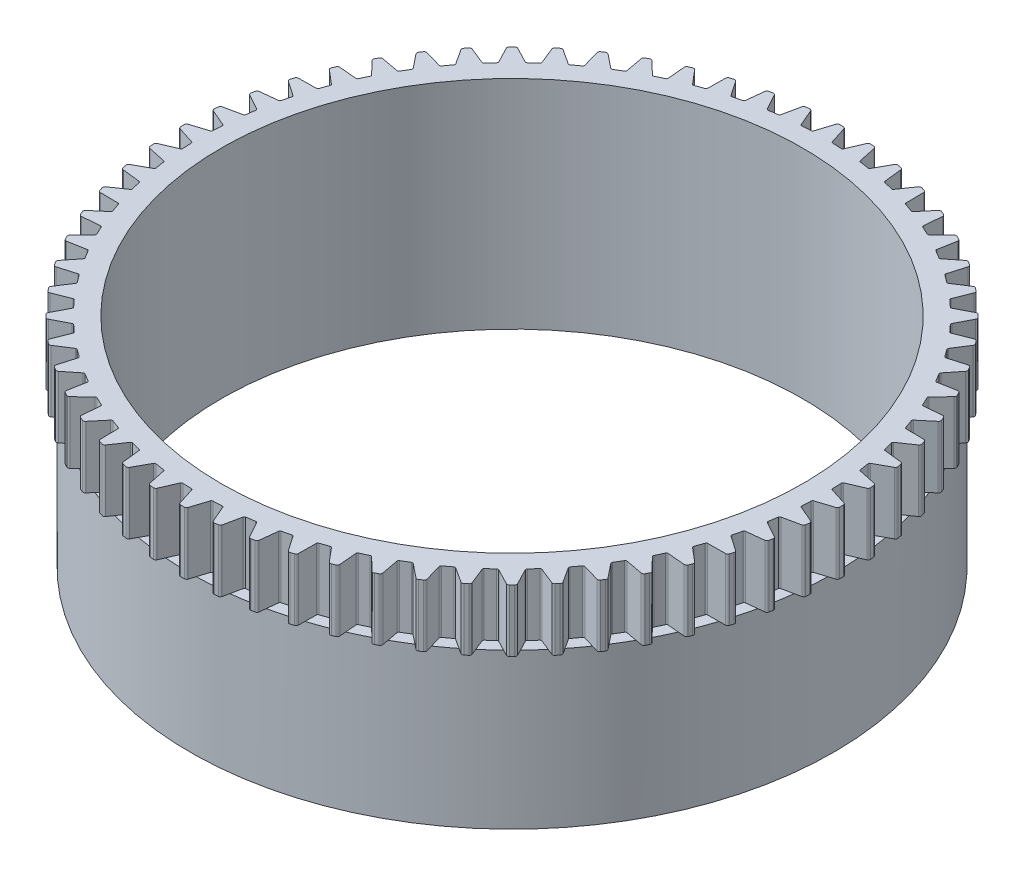
SolidWorks part; units mm, degrees
ref_plane "Front Plane" through (0, 0, 0) normal (0, 0, 1) x (1, 0, 0)
ref_plane "Top Plane" through (0, 0, 0) normal (0, 1, 0) x (1, 0, 0)
ref_plane "Right Plane" through (0, 0, 0) normal (1, 0, 0) x (0, 0, -1)
sketch "Sketch1" plane through (0, 0, 0) normal (0, 1, 0) x (1, 0, 0)
  line L0 (0, 53.7167) -> (0, -50.4595) construction
  line L1 (-0.5164, 42.2908) -> (-1.2072, 40.1152)
  line L2 (-0.2305, 42.5) -> (0.2305, 42.5)
  line L3 (0.5164, 42.2908) -> (1.2072, 40.1152)
  line L4 (3.6313, 42.1378) -> (2.7306, 40.0403)
  line L5 (4.6592, 42.0365) -> (5.1334, 39.8037)
  line L6 (3.9363, 42.3179) -> (4.3951, 42.2728)
  line L7 (7.744, 41.5789) -> (6.642, 39.5799)
  line L8 (8.757, 41.3774) -> (9.0101, 39.1088)
  line L9 (8.0653, 41.7283) -> (8.5174, 41.6384)
  line L10 (11.7822, 40.6197) -> (10.4896, 38.7383)
  line L11 (12.7706, 40.3199) -> (12.8001, 38.0374)
  line L12 (12.1165, 40.7369) -> (12.5577, 40.6031)
  line L13 (15.7069, 39.2692) -> (14.2361, 37.5236)
  line L14 (16.6611, 38.874) -> (16.4667, 36.5996)
  line L15 (16.0511, 39.3531) -> (16.477, 39.1767)
  line L16 (19.4803, 37.5406) -> (17.8455, 35.9475)
  line L17 (20.3912, 37.0537) -> (19.9748, 34.8093)
  line L18 (19.8311, 37.5903) -> (20.2376, 37.373)
  line L19 (23.0661, 35.4504) -> (21.283, 34.0252)
  line L20 (23.9249, 34.8766) -> (23.2906, 32.6838)
  line L21 (23.4201, 35.4655) -> (23.8034, 35.2094)
  line L22 (26.4298, 33.0188) -> (24.5156, 31.7753)
  line L23 (27.2282, 32.3636) -> (26.382, 30.2436)
  line L24 (26.7835, 32.9992) -> (27.1399, 32.7067)
  line L25 (29.5389, 30.2693) -> (27.5121, 29.2193)
  line L26 (30.2693, 29.5389) -> (29.2193, 27.5121)
  line L27 (29.8891, 30.215) -> (30.215, 29.8891)
  line L28 (32.3636, 27.2282) -> (30.2436, 26.382)
  line L29 (33.0188, 26.4298) -> (31.7753, 24.5156)
  line L30 (32.7067, 27.1399) -> (32.9992, 26.7835)
  line L31 (34.8766, 23.9249) -> (32.6838, 23.2906)
  line L32 (35.4504, 23.0661) -> (34.0252, 21.283)
  line L33 (35.2094, 23.8034) -> (35.4655, 23.4201)
  line L34 (37.0537, 20.3912) -> (34.8093, 19.9748)
  line L35 (37.5406, 19.4803) -> (35.9475, 17.8455)
  line L36 (37.373, 20.2376) -> (37.5903, 19.8311)
  line L37 (38.874, 16.6611) -> (36.5996, 16.4667)
  line L38 (39.2692, 15.7069) -> (37.5236, 14.2361)
  line L39 (39.1767, 16.477) -> (39.3531, 16.0511)
  line L40 (40.3199, 12.7706) -> (38.0374, 12.8001)
  line L41 (40.6197, 11.7822) -> (38.7383, 10.4896)
  line L42 (40.6031, 12.5577) -> (40.7369, 12.1165)
  line L43 (41.3774, 8.757) -> (39.1088, 9.0101)
  line L44 (41.5789, 7.744) -> (39.5799, 6.642)
  line L45 (41.6384, 8.5174) -> (41.7283, 8.0653)
  line L46 (42.0365, 4.6592) -> (39.8037, 5.1334)
  line L47 (42.1378, 3.6313) -> (40.0403, 2.7306)
  line L48 (42.2728, 4.3951) -> (42.3179, 3.9363)
  line L49 (42.2908, 0.5164) -> (40.1152, 1.2072)
  line L50 (42.2908, -0.5164) -> (40.1152, -1.2072)
  line L51 (42.5, 0.2305) -> (42.5, -0.2305)
  line L52 (42.1378, -3.6313) -> (40.0403, -2.7306)
  line L53 (42.0365, -4.6592) -> (39.8037, -5.1334)
  line L54 (42.3179, -3.9363) -> (42.2728, -4.3951)
  line L55 (41.5789, -7.744) -> (39.5799, -6.642)
  line L56 (41.3774, -8.757) -> (39.1088, -9.0101)
  line L57 (41.7283, -8.0653) -> (41.6384, -8.5174)
  line L58 (40.6197, -11.7822) -> (38.7383, -10.4896)
  line L59 (40.3199, -12.7706) -> (38.0374, -12.8001)
  line L60 (40.7369, -12.1165) -> (40.6031, -12.5577)
  line L61 (39.2692, -15.7069) -> (37.5236, -14.2361)
  line L62 (38.874, -16.6611) -> (36.5996, -16.4667)
  line L63 (39.3531, -16.0511) -> (39.1767, -16.477)
  line L64 (37.5406, -19.4803) -> (35.9475, -17.8455)
  line L65 (37.0537, -20.3912) -> (34.8093, -19.9748)
  line L66 (37.5903, -19.8311) -> (37.373, -20.2376)
  line L67 (35.4504, -23.0661) -> (34.0252, -21.283)
  line L68 (34.8766, -23.9249) -> (32.6838, -23.2906)
  line L69 (35.4655, -23.4201) -> (35.2094, -23.8034)
  line L70 (33.0188, -26.4298) -> (31.7753, -24.5156)
  line L71 (32.3636, -27.2282) -> (30.2436, -26.382)
  line L72 (32.9992, -26.7835) -> (32.7067, -27.1399)
  line L73 (30.2693, -29.5389) -> (29.2193, -27.5121)
  line L74 (29.5389, -30.2693) -> (27.5121, -29.2193)
  line L75 (30.215, -29.8891) -> (29.8891, -30.215)
  line L76 (27.2282, -32.3636) -> (26.382, -30.2436)
  line L77 (26.4298, -33.0188) -> (24.5156, -31.7753)
  line L78 (27.1399, -32.7067) -> (26.7835, -32.9992)
  line L79 (23.9249, -34.8766) -> (23.2906, -32.6838)
  line L80 (23.0661, -35.4504) -> (21.283, -34.0252)
  line L81 (23.8034, -35.2094) -> (23.4201, -35.4655)
  line L82 (20.3912, -37.0537) -> (19.9748, -34.8093)
  line L83 (19.4803, -37.5406) -> (17.8455, -35.9475)
  line L84 (20.2376, -37.373) -> (19.8311, -37.5903)
  line L85 (16.6611, -38.874) -> (16.4667, -36.5996)
  line L86 (15.7069, -39.2692) -> (14.2361, -37.5236)
  line L87 (16.477, -39.1767) -> (16.0511, -39.3531)
  line L88 (12.7706, -40.3199) -> (12.8001, -38.0374)
  line L89 (11.7822, -40.6197) -> (10.4896, -38.7383)
  line L90 (12.5577, -40.6031) -> (12.1165, -40.7369)
  line L91 (8.757, -41.3774) -> (9.0101, -39.1088)
  line L92 (7.744, -41.5789) -> (6.642, -39.5799)
  line L93 (8.5174, -41.6384) -> (8.0653, -41.7283)
  line L94 (4.6592, -42.0365) -> (5.1334, -39.8037)
  line L95 (3.6313, -42.1378) -> (2.7306, -40.0403)
  line L96 (4.3951, -42.2728) -> (3.9363, -42.3179)
  line L97 (0.5164, -42.2908) -> (1.2072, -40.1152)
  line L98 (-0.5164, -42.2908) -> (-1.2072, -40.1152)
  line L99 (0.2305, -42.5) -> (-0.2305, -42.5)
  line L100 (-3.6313, -42.1378) -> (-2.7306, -40.0403)
  line L101 (-4.6592, -42.0365) -> (-5.1334, -39.8037)
  line L102 (-3.9363, -42.3179) -> (-4.3951, -42.2728)
  line L103 (-7.744, -41.5789) -> (-6.642, -39.5799)
  line L104 (-8.757, -41.3774) -> (-9.0101, -39.1088)
  line L105 (-8.0653, -41.7283) -> (-8.5174, -41.6384)
  line L106 (-11.7822, -40.6197) -> (-10.4896, -38.7383)
  line L107 (-12.7706, -40.3199) -> (-12.8001, -38.0374)
  line L108 (-12.1165, -40.7369) -> (-12.5577, -40.6031)
  line L109 (-15.7069, -39.2692) -> (-14.2361, -37.5236)
  line L110 (-16.6611, -38.874) -> (-16.4667, -36.5996)
  line L111 (-16.0511, -39.3531) -> (-16.477, -39.1767)
  line L112 (-19.4803, -37.5406) -> (-17.8455, -35.9475)
  line L113 (-20.3912, -37.0537) -> (-19.9748, -34.8093)
  line L114 (-19.8311, -37.5903) -> (-20.2376, -37.373)
  line L115 (-23.0661, -35.4504) -> (-21.283, -34.0252)
  line L116 (-23.9249, -34.8766) -> (-23.2906, -32.6838)
  line L117 (-23.4201, -35.4655) -> (-23.8034, -35.2094)
  line L118 (-26.4298, -33.0188) -> (-24.5156, -31.7753)
  line L119 (-27.2282, -32.3636) -> (-26.382, -30.2436)
  line L120 (-26.7835, -32.9992) -> (-27.1399, -32.7067)
  line L121 (-29.5389, -30.2693) -> (-27.5121, -29.2193)
  line L122 (-30.2693, -29.5389) -> (-29.2193, -27.5121)
  line L123 (-29.8891, -30.215) -> (-30.215, -29.8891)
  line L124 (-32.3636, -27.2282) -> (-30.2436, -26.382)
  line L125 (-33.0188, -26.4298) -> (-31.7753, -24.5156)
  line L126 (-32.7067, -27.1399) -> (-32.9992, -26.7835)
  line L127 (-34.8766, -23.9249) -> (-32.6838, -23.2906)
  line L128 (-35.4504, -23.0661) -> (-34.0252, -21.283)
  line L129 (-35.2094, -23.8034) -> (-35.4655, -23.4201)
  line L130 (-37.0537, -20.3912) -> (-34.8093, -19.9748)
  line L131 (-37.5406, -19.4803) -> (-35.9475, -17.8455)
  line L132 (-37.373, -20.2376) -> (-37.5903, -19.8311)
  line L133 (-38.874, -16.6611) -> (-36.5996, -16.4667)
  line L134 (-39.2692, -15.7069) -> (-37.5236, -14.2361)
  line L135 (-39.1767, -16.477) -> (-39.3531, -16.0511)
  line L136 (-40.3199, -12.7706) -> (-38.0374, -12.8001)
  line L137 (-40.6197, -11.7822) -> (-38.7383, -10.4896)
  line L138 (-40.6031, -12.5577) -> (-40.7369, -12.1165)
  line L139 (-41.3774, -8.757) -> (-39.1088, -9.0101)
  line L140 (-41.5789, -7.744) -> (-39.5799, -6.642)
  line L141 (-41.6384, -8.5174) -> (-41.7283, -8.0653)
  line L142 (-42.0365, -4.6592) -> (-39.8037, -5.1334)
  line L143 (-42.1378, -3.6313) -> (-40.0403, -2.7306)
  line L144 (-42.2728, -4.3951) -> (-42.3179, -3.9363)
  line L145 (-42.2908, -0.5164) -> (-40.1152, -1.2072)
  line L146 (-42.2908, 0.5164) -> (-40.1152, 1.2072)
  line L147 (-42.5, -0.2305) -> (-42.5, 0.2305)
  line L148 (-42.1378, 3.6313) -> (-40.0403, 2.7306)
  line L149 (-42.0365, 4.6592) -> (-39.8037, 5.1334)
  line L150 (-42.3179, 3.9363) -> (-42.2728, 4.3951)
  line L151 (-41.5789, 7.744) -> (-39.5799, 6.642)
  line L152 (-41.3774, 8.757) -> (-39.1088, 9.0101)
  line L153 (-41.7283, 8.0653) -> (-41.6384, 8.5174)
  line L154 (-40.6197, 11.7822) -> (-38.7383, 10.4896)
  line L155 (-40.3199, 12.7706) -> (-38.0374, 12.8001)
  line L156 (-40.7369, 12.1165) -> (-40.6031, 12.5577)
  line L157 (-39.2692, 15.7069) -> (-37.5236, 14.2361)
  line L158 (-38.874, 16.6611) -> (-36.5996, 16.4667)
  line L159 (-39.3531, 16.0511) -> (-39.1767, 16.477)
  line L160 (-37.5406, 19.4803) -> (-35.9475, 17.8455)
  line L161 (-37.0537, 20.3912) -> (-34.8093, 19.9748)
  line L162 (-37.5903, 19.8311) -> (-37.373, 20.2376)
  line L163 (-35.4504, 23.0661) -> (-34.0252, 21.283)
  line L164 (-34.8766, 23.9249) -> (-32.6838, 23.2906)
  line L165 (-35.4655, 23.4201) -> (-35.2094, 23.8034)
  line L166 (-33.0188, 26.4298) -> (-31.7753, 24.5156)
  line L167 (-32.3636, 27.2282) -> (-30.2436, 26.382)
  line L168 (-32.9992, 26.7835) -> (-32.7067, 27.1399)
  line L169 (-30.2693, 29.5389) -> (-29.2193, 27.5121)
  line L170 (-29.5389, 30.2693) -> (-27.5121, 29.2193)
  line L171 (-30.215, 29.8891) -> (-29.8891, 30.215)
  line L172 (-27.2282, 32.3636) -> (-26.382, 30.2436)
  line L173 (-26.4298, 33.0188) -> (-24.5156, 31.7753)
  line L174 (-27.1399, 32.7067) -> (-26.7835, 32.9992)
  line L175 (-23.9249, 34.8766) -> (-23.2906, 32.6838)
  line L176 (-23.0661, 35.4504) -> (-21.283, 34.0252)
  line L177 (-23.8034, 35.2094) -> (-23.4201, 35.4655)
  line L178 (-20.3912, 37.0537) -> (-19.9748, 34.8093)
  line L179 (-19.4803, 37.5406) -> (-17.8455, 35.9475)
  line L180 (-20.2376, 37.373) -> (-19.8311, 37.5903)
  line L181 (-16.6611, 38.874) -> (-16.4667, 36.5996)
  line L182 (-15.7069, 39.2692) -> (-14.2361, 37.5236)
  line L183 (-16.477, 39.1767) -> (-16.0511, 39.3531)
  line L184 (-12.7706, 40.3199) -> (-12.8001, 38.0374)
  line L185 (-11.7822, 40.6197) -> (-10.4896, 38.7383)
  line L186 (-12.5577, 40.6031) -> (-12.1165, 40.7369)
  line L187 (-8.757, 41.3774) -> (-9.0101, 39.1088)
  line L188 (-7.744, 41.5789) -> (-6.642, 39.5799)
  line L189 (-8.5174, 41.6384) -> (-8.0653, 41.7283)
  line L190 (-4.6592, 42.0365) -> (-5.1334, 39.8037)
  line L191 (-3.6313, 42.1378) -> (-2.7306, 40.0403)
  line L192 (-4.3951, 42.2728) -> (-3.9363, 42.3179)
  arc A0 (-1.3909, 39.9758) -> (-2.5341, 39.9196) centre (0, 0) ccw
  arc A1 (-0.5164, 42.2908) -> (-0.2305, 42.5) centre (-0.2305, 42.2) cw
  arc A2 (0.2305, 42.5) -> (0.5164, 42.2908) centre (0.2305, 42.2) cw
  arc A3 (1.2072, 40.1152) -> (1.3909, 39.9758) centre (1.3979, 40.1757) ccw
  arc A4 (-1.2072, 40.1152) -> (-1.3909, 39.9758) centre (-1.3979, 40.1757) cw
  arc A5 (2.7306, 40.0403) -> (2.5341, 39.9196) centre (2.5468, 40.1192) cw
  arc A6 (5.1334, 39.8037) -> (5.3025, 39.647) centre (5.329, 39.8452) ccw
  arc A7 (4.3951, 42.2728) -> (4.6592, 42.0365) centre (4.3657, 41.9742) cw
  arc A8 (3.6313, 42.1378) -> (3.9363, 42.3179) centre (3.9069, 42.0194) cw
  arc A9 (6.642, 39.5799) -> (6.4347, 39.479) centre (6.4669, 39.6764) cw
  arc A10 (9.0101, 39.1088) -> (9.1631, 38.9363) centre (9.2089, 39.131) ccw
  arc A11 (8.5174, 41.6384) -> (8.757, 41.3774) centre (8.4589, 41.3442) cw
  arc A12 (7.744, 41.5789) -> (8.0653, 41.7283) centre (8.0067, 41.4341) cw
  arc A13 (10.4896, 38.7383) -> (10.2734, 38.6582) centre (10.3247, 38.8515) cw
  arc A14 (12.8001, 38.0374) -> (12.9354, 37.8507) centre (13, 38.04) ccw
  arc A15 (12.5577, 40.6031) -> (12.7706, 40.3199) centre (12.4706, 40.316) cw
  arc A16 (11.7822, 40.6197) -> (12.1165, 40.7369) centre (12.0294, 40.4498) cw
  arc A17 (14.2361, 37.5236) -> (14.0131, 37.4651) centre (14.0831, 37.6524) cw
  arc A18 (16.4667, 36.5996) -> (16.5831, 36.4006) centre (16.666, 36.5826) ccw
  arc A19 (16.477, 39.1767) -> (16.6611, 38.874) centre (16.3622, 38.8995) cw
  arc A20 (15.7069, 39.2692) -> (16.0511, 39.3531) centre (15.9363, 39.0759) cw
  arc A21 (17.8455, 35.9475) -> (17.6178, 35.9112) centre (17.7059, 36.0907) cw
  arc A22 (19.9748, 34.8093) -> (20.0711, 34.5999) centre (20.1715, 34.7729) ccw
  arc A23 (20.2376, 37.373) -> (20.3912, 37.0537) centre (20.0962, 37.1084) cw
  arc A24 (19.4803, 37.5406) -> (19.8311, 37.5903) centre (19.6897, 37.3257) cw
  arc A25 (21.283, 34.0252) -> (21.0529, 34.0114) centre (21.1581, 34.1815) cw
  arc A26 (23.2906, 32.6838) -> (23.3659, 32.4659) centre (23.4827, 32.6283) ccw
  arc A27 (23.8034, 35.2094) -> (23.9249, 34.8766) centre (23.6367, 34.96) cw
  arc A28 (23.0661, 35.4504) -> (23.4201, 35.4655) centre (23.2534, 35.2161) cw
  arc A29 (24.5156, 31.7753) -> (24.2852, 31.7841) centre (24.4066, 31.943) cw
  arc A30 (26.382, 30.2436) -> (26.4356, 30.0193) centre (26.5677, 30.1694) ccw
  arc A31 (27.1399, 32.7067) -> (27.2282, 32.3636) centre (26.9496, 32.4748) cw
  arc A32 (26.4298, 33.0188) -> (26.7835, 32.9992) centre (26.5932, 32.7673) cw
  arc A33 (27.5121, 29.2193) -> (27.2837, 29.2507) centre (27.4201, 29.3969) cw
  arc A34 (29.2193, 27.5121) -> (29.2507, 27.2837) centre (29.3969, 27.4201) ccw
  arc A35 (30.215, 29.8891) -> (30.2693, 29.5389) centre (30.0029, 29.6769) cw
  arc A36 (29.5389, 30.2693) -> (29.8891, 30.215) centre (29.6769, 30.0029) cw
  arc A37 (30.2436, 26.382) -> (30.0193, 26.4356) centre (30.1694, 26.5677) cw
  arc A38 (31.7753, 24.5156) -> (31.7841, 24.2852) centre (31.943, 24.4066) ccw
  arc A39 (32.9992, 26.7835) -> (33.0188, 26.4298) centre (32.7673, 26.5932) cw
  arc A40 (32.3636, 27.2282) -> (32.7067, 27.1399) centre (32.4748, 26.9496) cw
  arc A41 (32.6838, 23.2906) -> (32.4659, 23.3659) centre (32.6283, 23.4827) cw
  arc A42 (34.0252, 21.283) -> (34.0114, 21.0529) centre (34.1815, 21.1581) ccw
  arc A43 (35.4655, 23.4201) -> (35.4504, 23.0661) centre (35.2161, 23.2534) cw
  arc A44 (34.8766, 23.9249) -> (35.2094, 23.8034) centre (34.96, 23.6367) cw
  arc A45 (34.8093, 19.9748) -> (34.5999, 20.0711) centre (34.7729, 20.1715) cw
  arc A46 (35.9475, 17.8455) -> (35.9112, 17.6178) centre (36.0907, 17.7059) ccw
  arc A47 (37.5903, 19.8311) -> (37.5406, 19.4803) centre (37.3257, 19.6897) cw
  arc A48 (37.0537, 20.3912) -> (37.373, 20.2376) centre (37.1084, 20.0962) cw
  arc A49 (36.5996, 16.4667) -> (36.4006, 16.5831) centre (36.5826, 16.666) cw
  arc A50 (37.5236, 14.2361) -> (37.4651, 14.0131) centre (37.6524, 14.0831) ccw
  arc A51 (39.3531, 16.0511) -> (39.2692, 15.7069) centre (39.0759, 15.9363) cw
  arc A52 (38.874, 16.6611) -> (39.1767, 16.477) centre (38.8995, 16.3622) cw
  arc A53 (38.0374, 12.8001) -> (37.8507, 12.9354) centre (38.04, 13) cw
  arc A54 (38.7383, 10.4896) -> (38.6582, 10.2734) centre (38.8515, 10.3247) ccw
  arc A55 (40.7369, 12.1165) -> (40.6197, 11.7822) centre (40.4498, 12.0294) cw
  arc A56 (40.3199, 12.7706) -> (40.6031, 12.5577) centre (40.316, 12.4706) cw
  arc A57 (39.1088, 9.0101) -> (38.9363, 9.1631) centre (39.131, 9.2089) cw
  arc A58 (39.5799, 6.642) -> (39.479, 6.4347) centre (39.6764, 6.4669) ccw
  arc A59 (41.7283, 8.0653) -> (41.5789, 7.744) centre (41.4341, 8.0067) cw
  arc A60 (41.3774, 8.757) -> (41.6384, 8.5174) centre (41.3442, 8.4589) cw
  arc A61 (39.8037, 5.1334) -> (39.647, 5.3025) centre (39.8452, 5.329) cw
  arc A62 (40.0403, 2.7306) -> (39.9196, 2.5341) centre (40.1192, 2.5468) ccw
  arc A63 (42.3179, 3.9363) -> (42.1378, 3.6313) centre (42.0194, 3.9069) cw
  arc A64 (42.0365, 4.6592) -> (42.2728, 4.3951) centre (41.9742, 4.3657) cw
  arc A65 (40.1152, 1.2072) -> (39.9758, 1.3909) centre (40.1757, 1.3979) cw
  arc A66 (40.1152, -1.2072) -> (39.9758, -1.3909) centre (40.1757, -1.3979) ccw
  arc A67 (42.5, -0.2305) -> (42.2908, -0.5164) centre (42.2, -0.2305) cw
  arc A68 (42.2908, 0.5164) -> (42.5, 0.2305) centre (42.2, 0.2305) cw
  arc A69 (40.0403, -2.7306) -> (39.9196, -2.5341) centre (40.1192, -2.5468) cw
  arc A70 (39.8037, -5.1334) -> (39.647, -5.3025) centre (39.8452, -5.329) ccw
  arc A71 (42.2728, -4.3951) -> (42.0365, -4.6592) centre (41.9742, -4.3657) cw
  arc A72 (42.1378, -3.6313) -> (42.3179, -3.9363) centre (42.0194, -3.9069) cw
  arc A73 (39.5799, -6.642) -> (39.479, -6.4347) centre (39.6764, -6.4669) cw
  arc A74 (39.1088, -9.0101) -> (38.9363, -9.1631) centre (39.131, -9.2089) ccw
  arc A75 (41.6384, -8.5174) -> (41.3774, -8.757) centre (41.3442, -8.4589) cw
  arc A76 (41.5789, -7.744) -> (41.7283, -8.0653) centre (41.4341, -8.0067) cw
  arc A77 (38.7383, -10.4896) -> (38.6582, -10.2734) centre (38.8515, -10.3247) cw
  arc A78 (38.0374, -12.8001) -> (37.8507, -12.9354) centre (38.04, -13) ccw
  arc A79 (40.6031, -12.5577) -> (40.3199, -12.7706) centre (40.316, -12.4706) cw
  arc A80 (40.6197, -11.7822) -> (40.7369, -12.1165) centre (40.4498, -12.0294) cw
  arc A81 (37.5236, -14.2361) -> (37.4651, -14.0131) centre (37.6524, -14.0831) cw
  arc A82 (36.5996, -16.4667) -> (36.4006, -16.5831) centre (36.5826, -16.666) ccw
  arc A83 (39.1767, -16.477) -> (38.874, -16.6611) centre (38.8995, -16.3622) cw
  arc A84 (39.2692, -15.7069) -> (39.3531, -16.0511) centre (39.0759, -15.9363) cw
  arc A85 (35.9475, -17.8455) -> (35.9112, -17.6178) centre (36.0907, -17.7059) cw
  arc A86 (34.8093, -19.9748) -> (34.5999, -20.0711) centre (34.7729, -20.1715) ccw
  arc A87 (37.373, -20.2376) -> (37.0537, -20.3912) centre (37.1084, -20.0962) cw
  arc A88 (37.5406, -19.4803) -> (37.5903, -19.8311) centre (37.3257, -19.6897) cw
  arc A89 (34.0252, -21.283) -> (34.0114, -21.0529) centre (34.1815, -21.1581) cw
  arc A90 (32.6838, -23.2906) -> (32.4659, -23.3659) centre (32.6283, -23.4827) ccw
  arc A91 (35.2094, -23.8034) -> (34.8766, -23.9249) centre (34.96, -23.6367) cw
  arc A92 (35.4504, -23.0661) -> (35.4655, -23.4201) centre (35.2161, -23.2534) cw
  arc A93 (31.7753, -24.5156) -> (31.7841, -24.2852) centre (31.943, -24.4066) cw
  arc A94 (30.2436, -26.382) -> (30.0193, -26.4356) centre (30.1694, -26.5677) ccw
  arc A95 (32.7067, -27.1399) -> (32.3636, -27.2282) centre (32.4748, -26.9496) cw
  arc A96 (33.0188, -26.4298) -> (32.9992, -26.7835) centre (32.7673, -26.5932) cw
  arc A97 (29.2193, -27.5121) -> (29.2507, -27.2837) centre (29.3969, -27.4201) cw
  arc A98 (27.5121, -29.2193) -> (27.2837, -29.2507) centre (27.4201, -29.3969) ccw
  arc A99 (29.8891, -30.215) -> (29.5389, -30.2693) centre (29.6769, -30.0029) cw
  arc A100 (30.2693, -29.5389) -> (30.215, -29.8891) centre (30.0029, -29.6769) cw
  arc A101 (26.382, -30.2436) -> (26.4356, -30.0193) centre (26.5677, -30.1694) cw
  arc A102 (24.5156, -31.7753) -> (24.2852, -31.7841) centre (24.4066, -31.943) ccw
  arc A103 (26.7835, -32.9992) -> (26.4298, -33.0188) centre (26.5932, -32.7673) cw
  arc A104 (27.2282, -32.3636) -> (27.1399, -32.7067) centre (26.9496, -32.4748) cw
  arc A105 (23.2906, -32.6838) -> (23.3659, -32.4659) centre (23.4827, -32.6283) cw
  arc A106 (21.283, -34.0252) -> (21.0529, -34.0114) centre (21.1581, -34.1815) ccw
  arc A107 (23.4201, -35.4655) -> (23.0661, -35.4504) centre (23.2534, -35.2161) cw
  arc A108 (23.9249, -34.8766) -> (23.8034, -35.2094) centre (23.6367, -34.96) cw
  arc A109 (19.9748, -34.8093) -> (20.0711, -34.5999) centre (20.1715, -34.7729) cw
  arc A110 (17.8455, -35.9475) -> (17.6178, -35.9112) centre (17.7059, -36.0907) ccw
  arc A111 (19.8311, -37.5903) -> (19.4803, -37.5406) centre (19.6897, -37.3257) cw
  arc A112 (20.3912, -37.0537) -> (20.2376, -37.373) centre (20.0962, -37.1084) cw
  arc A113 (16.4667, -36.5996) -> (16.5831, -36.4006) centre (16.666, -36.5826) cw
  arc A114 (14.2361, -37.5236) -> (14.0131, -37.4651) centre (14.0831, -37.6524) ccw
  arc A115 (16.0511, -39.3531) -> (15.7069, -39.2692) centre (15.9363, -39.0759) cw
  arc A116 (16.6611, -38.874) -> (16.477, -39.1767) centre (16.3622, -38.8995) cw
  arc A117 (12.8001, -38.0374) -> (12.9354, -37.8507) centre (13, -38.04) cw
  arc A118 (10.4896, -38.7383) -> (10.2734, -38.6582) centre (10.3247, -38.8515) ccw
  arc A119 (12.1165, -40.7369) -> (11.7822, -40.6197) centre (12.0294, -40.4498) cw
  arc A120 (12.7706, -40.3199) -> (12.5577, -40.6031) centre (12.4706, -40.316) cw
  arc A121 (9.0101, -39.1088) -> (9.1631, -38.9363) centre (9.2089, -39.131) cw
  arc A122 (6.642, -39.5799) -> (6.4347, -39.479) centre (6.4669, -39.6764) ccw
  arc A123 (8.0653, -41.7283) -> (7.744, -41.5789) centre (8.0067, -41.4341) cw
  arc A124 (8.757, -41.3774) -> (8.5174, -41.6384) centre (8.4589, -41.3442) cw
  arc A125 (5.1334, -39.8037) -> (5.3025, -39.647) centre (5.329, -39.8452) cw
  arc A126 (2.7306, -40.0403) -> (2.5341, -39.9196) centre (2.5468, -40.1192) ccw
  arc A127 (3.9363, -42.3179) -> (3.6313, -42.1378) centre (3.9069, -42.0194) cw
  arc A128 (4.6592, -42.0365) -> (4.3951, -42.2728) centre (4.3657, -41.9742) cw
  arc A129 (1.2072, -40.1152) -> (1.3909, -39.9758) centre (1.3979, -40.1757) cw
  arc A130 (-1.2072, -40.1152) -> (-1.3909, -39.9758) centre (-1.3979, -40.1757) ccw
  arc A131 (-0.2305, -42.5) -> (-0.5164, -42.2908) centre (-0.2305, -42.2) cw
  arc A132 (0.5164, -42.2908) -> (0.2305, -42.5) centre (0.2305, -42.2) cw
  arc A133 (-2.7306, -40.0403) -> (-2.5341, -39.9196) centre (-2.5468, -40.1192) cw
  arc A134 (-5.1334, -39.8037) -> (-5.3025, -39.647) centre (-5.329, -39.8452) ccw
  arc A135 (-4.3951, -42.2728) -> (-4.6592, -42.0365) centre (-4.3657, -41.9742) cw
  arc A136 (-3.6313, -42.1378) -> (-3.9363, -42.3179) centre (-3.9069, -42.0194) cw
  arc A137 (-6.642, -39.5799) -> (-6.4347, -39.479) centre (-6.4669, -39.6764) cw
  arc A138 (-9.0101, -39.1088) -> (-9.1631, -38.9363) centre (-9.2089, -39.131) ccw
  arc A139 (-8.5174, -41.6384) -> (-8.757, -41.3774) centre (-8.4589, -41.3442) cw
  arc A140 (-7.744, -41.5789) -> (-8.0653, -41.7283) centre (-8.0067, -41.4341) cw
  arc A141 (-10.4896, -38.7383) -> (-10.2734, -38.6582) centre (-10.3247, -38.8515) cw
  arc A142 (-12.8001, -38.0374) -> (-12.9354, -37.8507) centre (-13, -38.04) ccw
  arc A143 (-12.5577, -40.6031) -> (-12.7706, -40.3199) centre (-12.4706, -40.316) cw
  arc A144 (-11.7822, -40.6197) -> (-12.1165, -40.7369) centre (-12.0294, -40.4498) cw
  arc A145 (-14.2361, -37.5236) -> (-14.0131, -37.4651) centre (-14.0831, -37.6524) cw
  arc A146 (-16.4667, -36.5996) -> (-16.5831, -36.4006) centre (-16.666, -36.5826) ccw
  arc A147 (-16.477, -39.1767) -> (-16.6611, -38.874) centre (-16.3622, -38.8995) cw
  arc A148 (-15.7069, -39.2692) -> (-16.0511, -39.3531) centre (-15.9363, -39.0759) cw
  arc A149 (-17.8455, -35.9475) -> (-17.6178, -35.9112) centre (-17.7059, -36.0907) cw
  arc A150 (-19.9748, -34.8093) -> (-20.0711, -34.5999) centre (-20.1715, -34.7729) ccw
  arc A151 (-20.2376, -37.373) -> (-20.3912, -37.0537) centre (-20.0962, -37.1084) cw
  arc A152 (-19.4803, -37.5406) -> (-19.8311, -37.5903) centre (-19.6897, -37.3257) cw
  arc A153 (-21.283, -34.0252) -> (-21.0529, -34.0114) centre (-21.1581, -34.1815) cw
  arc A154 (-23.2906, -32.6838) -> (-23.3659, -32.4659) centre (-23.4827, -32.6283) ccw
  arc A155 (-23.8034, -35.2094) -> (-23.9249, -34.8766) centre (-23.6367, -34.96) cw
  arc A156 (-23.0661, -35.4504) -> (-23.4201, -35.4655) centre (-23.2534, -35.2161) cw
  arc A157 (-24.5156, -31.7753) -> (-24.2852, -31.7841) centre (-24.4066, -31.943) cw
  arc A158 (-26.382, -30.2436) -> (-26.4356, -30.0193) centre (-26.5677, -30.1694) ccw
  arc A159 (-27.1399, -32.7067) -> (-27.2282, -32.3636) centre (-26.9496, -32.4748) cw
  arc A160 (-26.4298, -33.0188) -> (-26.7835, -32.9992) centre (-26.5932, -32.7673) cw
  arc A161 (-27.5121, -29.2193) -> (-27.2837, -29.2507) centre (-27.4201, -29.3969) cw
  arc A162 (-29.2193, -27.5121) -> (-29.2507, -27.2837) centre (-29.3969, -27.4201) ccw
  arc A163 (-30.215, -29.8891) -> (-30.2693, -29.5389) centre (-30.0029, -29.6769) cw
  arc A164 (-29.5389, -30.2693) -> (-29.8891, -30.215) centre (-29.6769, -30.0029) cw
  arc A165 (-30.2436, -26.382) -> (-30.0193, -26.4356) centre (-30.1694, -26.5677) cw
  arc A166 (-31.7753, -24.5156) -> (-31.7841, -24.2852) centre (-31.943, -24.4066) ccw
  arc A167 (-32.9992, -26.7835) -> (-33.0188, -26.4298) centre (-32.7673, -26.5932) cw
  arc A168 (-32.3636, -27.2282) -> (-32.7067, -27.1399) centre (-32.4748, -26.9496) cw
  arc A169 (-32.6838, -23.2906) -> (-32.4659, -23.3659) centre (-32.6283, -23.4827) cw
  arc A170 (-34.0252, -21.283) -> (-34.0114, -21.0529) centre (-34.1815, -21.1581) ccw
  arc A171 (-35.4655, -23.4201) -> (-35.4504, -23.0661) centre (-35.2161, -23.2534) cw
  arc A172 (-34.8766, -23.9249) -> (-35.2094, -23.8034) centre (-34.96, -23.6367) cw
  arc A173 (-34.8093, -19.9748) -> (-34.5999, -20.0711) centre (-34.7729, -20.1715) cw
  arc A174 (-35.9475, -17.8455) -> (-35.9112, -17.6178) centre (-36.0907, -17.7059) ccw
  arc A175 (-37.5903, -19.8311) -> (-37.5406, -19.4803) centre (-37.3257, -19.6897) cw
  arc A176 (-37.0537, -20.3912) -> (-37.373, -20.2376) centre (-37.1084, -20.0962) cw
  arc A177 (-36.5996, -16.4667) -> (-36.4006, -16.5831) centre (-36.5826, -16.666) cw
  arc A178 (-37.5236, -14.2361) -> (-37.4651, -14.0131) centre (-37.6524, -14.0831) ccw
  arc A179 (-39.3531, -16.0511) -> (-39.2692, -15.7069) centre (-39.0759, -15.9363) cw
  arc A180 (-38.874, -16.6611) -> (-39.1767, -16.477) centre (-38.8995, -16.3622) cw
  arc A181 (-38.0374, -12.8001) -> (-37.8507, -12.9354) centre (-38.04, -13) cw
  arc A182 (-38.7383, -10.4896) -> (-38.6582, -10.2734) centre (-38.8515, -10.3247) ccw
  arc A183 (-40.7369, -12.1165) -> (-40.6197, -11.7822) centre (-40.4498, -12.0294) cw
  arc A184 (-40.3199, -12.7706) -> (-40.6031, -12.5577) centre (-40.316, -12.4706) cw
  arc A185 (-39.1088, -9.0101) -> (-38.9363, -9.1631) centre (-39.131, -9.2089) cw
  arc A186 (-39.5799, -6.642) -> (-39.479, -6.4347) centre (-39.6764, -6.4669) ccw
  arc A187 (-41.7283, -8.0653) -> (-41.5789, -7.744) centre (-41.4341, -8.0067) cw
  arc A188 (-41.3774, -8.757) -> (-41.6384, -8.5174) centre (-41.3442, -8.4589) cw
  arc A189 (-39.8037, -5.1334) -> (-39.647, -5.3025) centre (-39.8452, -5.329) cw
  arc A190 (-40.0403, -2.7306) -> (-39.9196, -2.5341) centre (-40.1192, -2.5468) ccw
  arc A191 (-42.3179, -3.9363) -> (-42.1378, -3.6313) centre (-42.0194, -3.9069) cw
  arc A192 (-42.0365, -4.6592) -> (-42.2728, -4.3951) centre (-41.9742, -4.3657) cw
  arc A193 (-40.1152, -1.2072) -> (-39.9758, -1.3909) centre (-40.1757, -1.3979) cw
  arc A194 (-40.1152, 1.2072) -> (-39.9758, 1.3909) centre (-40.1757, 1.3979) ccw
  arc A195 (-42.5, 0.2305) -> (-42.2908, 0.5164) centre (-42.2, 0.2305) cw
  arc A196 (-42.2908, -0.5164) -> (-42.5, -0.2305) centre (-42.2, -0.2305) cw
  arc A197 (-40.0403, 2.7306) -> (-39.9196, 2.5341) centre (-40.1192, 2.5468) cw
  arc A198 (-39.8037, 5.1334) -> (-39.647, 5.3025) centre (-39.8452, 5.329) ccw
  arc A199 (-42.2728, 4.3951) -> (-42.0365, 4.6592) centre (-41.9742, 4.3657) cw
  arc A200 (-42.1378, 3.6313) -> (-42.3179, 3.9363) centre (-42.0194, 3.9069) cw
  arc A201 (-39.5799, 6.642) -> (-39.479, 6.4347) centre (-39.6764, 6.4669) cw
  arc A202 (-39.1088, 9.0101) -> (-38.9363, 9.1631) centre (-39.131, 9.2089) ccw
  arc A203 (-41.6384, 8.5174) -> (-41.3774, 8.757) centre (-41.3442, 8.4589) cw
  arc A204 (-41.5789, 7.744) -> (-41.7283, 8.0653) centre (-41.4341, 8.0067) cw
  arc A205 (-38.7383, 10.4896) -> (-38.6582, 10.2734) centre (-38.8515, 10.3247) cw
  arc A206 (-38.0374, 12.8001) -> (-37.8507, 12.9354) centre (-38.04, 13) ccw
  arc A207 (-40.6031, 12.5577) -> (-40.3199, 12.7706) centre (-40.316, 12.4706) cw
  arc A208 (-40.6197, 11.7822) -> (-40.7369, 12.1165) centre (-40.4498, 12.0294) cw
  arc A209 (-37.5236, 14.2361) -> (-37.4651, 14.0131) centre (-37.6524, 14.0831) cw
  arc A210 (-36.5996, 16.4667) -> (-36.4006, 16.5831) centre (-36.5826, 16.666) ccw
  arc A211 (-39.1767, 16.477) -> (-38.874, 16.6611) centre (-38.8995, 16.3622) cw
  arc A212 (-39.2692, 15.7069) -> (-39.3531, 16.0511) centre (-39.0759, 15.9363) cw
  arc A213 (-35.9475, 17.8455) -> (-35.9112, 17.6178) centre (-36.0907, 17.7059) cw
  arc A214 (-34.8093, 19.9748) -> (-34.5999, 20.0711) centre (-34.7729, 20.1715) ccw
  arc A215 (-37.373, 20.2376) -> (-37.0537, 20.3912) centre (-37.1084, 20.0962) cw
  arc A216 (-37.5406, 19.4803) -> (-37.5903, 19.8311) centre (-37.3257, 19.6897) cw
  arc A217 (-34.0252, 21.283) -> (-34.0114, 21.0529) centre (-34.1815, 21.1581) cw
  arc A218 (-32.6838, 23.2906) -> (-32.4659, 23.3659) centre (-32.6283, 23.4827) ccw
  arc A219 (-35.2094, 23.8034) -> (-34.8766, 23.9249) centre (-34.96, 23.6367) cw
  arc A220 (-35.4504, 23.0661) -> (-35.4655, 23.4201) centre (-35.2161, 23.2534) cw
  arc A221 (-31.7753, 24.5156) -> (-31.7841, 24.2852) centre (-31.943, 24.4066) cw
  arc A222 (-30.2436, 26.382) -> (-30.0193, 26.4356) centre (-30.1694, 26.5677) ccw
  arc A223 (-32.7067, 27.1399) -> (-32.3636, 27.2282) centre (-32.4748, 26.9496) cw
  arc A224 (-33.0188, 26.4298) -> (-32.9992, 26.7835) centre (-32.7673, 26.5932) cw
  arc A225 (-29.2193, 27.5121) -> (-29.2507, 27.2837) centre (-29.3969, 27.4201) cw
  arc A226 (-27.5121, 29.2193) -> (-27.2837, 29.2507) centre (-27.4201, 29.3969) ccw
  arc A227 (-29.8891, 30.215) -> (-29.5389, 30.2693) centre (-29.6769, 30.0029) cw
  arc A228 (-30.2693, 29.5389) -> (-30.215, 29.8891) centre (-30.0029, 29.6769) cw
  arc A229 (-26.382, 30.2436) -> (-26.4356, 30.0193) centre (-26.5677, 30.1694) cw
  arc A230 (-24.5156, 31.7753) -> (-24.2852, 31.7841) centre (-24.4066, 31.943) ccw
  arc A231 (-26.7835, 32.9992) -> (-26.4298, 33.0188) centre (-26.5932, 32.7673) cw
  arc A232 (-27.2282, 32.3636) -> (-27.1399, 32.7067) centre (-26.9496, 32.4748) cw
  arc A233 (-23.2906, 32.6838) -> (-23.3659, 32.4659) centre (-23.4827, 32.6283) cw
  arc A234 (-21.283, 34.0252) -> (-21.0529, 34.0114) centre (-21.1581, 34.1815) ccw
  arc A235 (-23.4201, 35.4655) -> (-23.0661, 35.4504) centre (-23.2534, 35.2161) cw
  arc A236 (-23.9249, 34.8766) -> (-23.8034, 35.2094) centre (-23.6367, 34.96) cw
  arc A237 (-19.9748, 34.8093) -> (-20.0711, 34.5999) centre (-20.1715, 34.7729) cw
  arc A238 (-17.8455, 35.9475) -> (-17.6178, 35.9112) centre (-17.7059, 36.0907) ccw
  arc A239 (-19.8311, 37.5903) -> (-19.4803, 37.5406) centre (-19.6897, 37.3257) cw
  arc A240 (-20.3912, 37.0537) -> (-20.2376, 37.373) centre (-20.0962, 37.1084) cw
  arc A241 (-16.4667, 36.5996) -> (-16.5831, 36.4006) centre (-16.666, 36.5826) cw
  arc A242 (-14.2361, 37.5236) -> (-14.0131, 37.4651) centre (-14.0831, 37.6524) ccw
  arc A243 (-16.0511, 39.3531) -> (-15.7069, 39.2692) centre (-15.9363, 39.0759) cw
  arc A244 (-16.6611, 38.874) -> (-16.477, 39.1767) centre (-16.3622, 38.8995) cw
  arc A245 (-12.8001, 38.0374) -> (-12.9354, 37.8507) centre (-13, 38.04) cw
  arc A246 (-10.4896, 38.7383) -> (-10.2734, 38.6582) centre (-10.3247, 38.8515) ccw
  arc A247 (-12.1165, 40.7369) -> (-11.7822, 40.6197) centre (-12.0294, 40.4498) cw
  arc A248 (-12.7706, 40.3199) -> (-12.5577, 40.6031) centre (-12.4706, 40.316) cw
  arc A249 (-9.0101, 39.1088) -> (-9.1631, 38.9363) centre (-9.2089, 39.131) cw
  arc A250 (-6.642, 39.5799) -> (-6.4347, 39.479) centre (-6.4669, 39.6764) ccw
  arc A251 (-8.0653, 41.7283) -> (-7.744, 41.5789) centre (-8.0067, 41.4341) cw
  arc A252 (-8.757, 41.3774) -> (-8.5174, 41.6384) centre (-8.4589, 41.3442) cw
  arc A253 (-5.1334, 39.8037) -> (-5.3025, 39.647) centre (-5.329, 39.8452) cw
  arc A254 (-2.7306, 40.0403) -> (-2.5341, 39.9196) centre (-2.5468, 40.1192) ccw
  arc A255 (-3.9363, 42.3179) -> (-3.6313, 42.1378) centre (-3.9069, 42.0194) cw
  arc A256 (-4.6592, 42.0365) -> (-4.3951, 42.2728) centre (-4.3657, 41.9742) cw
  arc A257 (-5.3025, 39.647) -> (-6.4347, 39.479) centre (0, 0) ccw
  arc A258 (-9.1631, 38.9363) -> (-10.2734, 38.6582) centre (0, 0) ccw
  arc A259 (-12.9354, 37.8507) -> (-14.0131, 37.4651) centre (0, 0) ccw
  arc A260 (-16.5831, 36.4006) -> (-17.6178, 35.9112) centre (0, 0) ccw
  arc A261 (-20.0711, 34.5999) -> (-21.0529, 34.0114) centre (0, 0) ccw
  arc A262 (-23.3659, 32.4659) -> (-24.2852, 31.7841) centre (0, 0) ccw
  arc A263 (-26.4356, 30.0193) -> (-27.2837, 29.2507) centre (0, 0) ccw
  arc A264 (-29.2507, 27.2837) -> (-30.0193, 26.4356) centre (0, 0) ccw
  arc A265 (-34.0114, 21.0529) -> (-34.5999, 20.0711) centre (0, 0) ccw
  arc A266 (-31.7841, 24.2852) -> (-32.4659, 23.3659) centre (0, 0) ccw
  arc A267 (-35.9112, 17.6178) -> (-36.4006, 16.5831) centre (0, 0) ccw
  arc A268 (-37.4651, 14.0131) -> (-37.8507, 12.9354) centre (0, 0) ccw
  arc A269 (-38.6582, 10.2734) -> (-38.9363, 9.1631) centre (0, 0) ccw
  arc A270 (-39.479, 6.4347) -> (-39.647, 5.3025) centre (0, 0) ccw
  arc A271 (-39.9196, 2.5341) -> (-39.9758, 1.3909) centre (0, 0) ccw
  arc A272 (-39.9758, -1.3909) -> (-39.9196, -2.5341) centre (0, 0) ccw
  arc A273 (-39.647, -5.3025) -> (-39.479, -6.4347) centre (0, 0) ccw
  arc A274 (-38.9363, -9.1631) -> (-38.6582, -10.2734) centre (0, 0) ccw
  arc A275 (-37.8507, -12.9354) -> (-37.4651, -14.0131) centre (0, 0) ccw
  arc A276 (-36.4006, -16.5831) -> (-35.9112, -17.6178) centre (0, 0) ccw
  arc A277 (-34.5999, -20.0711) -> (-34.0114, -21.0529) centre (0, 0) ccw
  arc A278 (-32.4659, -23.3659) -> (-31.7841, -24.2852) centre (0, 0) ccw
  arc A279 (-30.0193, -26.4356) -> (-29.2507, -27.2837) centre (0, 0) ccw
  arc A280 (-27.2837, -29.2507) -> (-26.4356, -30.0193) centre (0, 0) ccw
  arc A281 (-17.6178, -35.9112) -> (-16.5831, -36.4006) centre (0, 0) ccw
  arc A282 (-21.0529, -34.0114) -> (-20.0711, -34.5999) centre (0, 0) ccw
  arc A283 (-24.2852, -31.7841) -> (-23.3659, -32.4659) centre (0, 0) ccw
  arc A284 (-14.0131, -37.4651) -> (-12.9354, -37.8507) centre (0, 0) ccw
  arc A285 (-10.2734, -38.6582) -> (-9.1631, -38.9363) centre (0, 0) ccw
  arc A286 (-6.4347, -39.479) -> (-5.3025, -39.647) centre (0, 0) ccw
  arc A287 (-2.5341, -39.9196) -> (-1.3909, -39.9758) centre (0, 0) ccw
  arc A288 (1.3909, -39.9758) -> (2.5341, -39.9196) centre (0, 0) ccw
  arc A289 (5.3025, -39.647) -> (6.4347, -39.479) centre (0, 0) ccw
  arc A290 (9.1631, -38.9363) -> (10.2734, -38.6582) centre (0, 0) ccw
  arc A291 (12.9354, -37.8507) -> (14.0131, -37.4651) centre (0, 0) ccw
  arc A292 (16.5831, -36.4006) -> (17.6178, -35.9112) centre (0, 0) ccw
  arc A293 (20.0711, -34.5999) -> (21.0529, -34.0114) centre (0, 0) ccw
  arc A294 (23.3659, -32.4659) -> (24.2852, -31.7841) centre (0, 0) ccw
  arc A295 (26.4356, -30.0193) -> (27.2837, -29.2507) centre (0, 0) ccw
  arc A296 (29.2507, -27.2837) -> (30.0193, -26.4356) centre (0, 0) ccw
  arc A297 (31.7841, -24.2852) -> (32.4659, -23.3659) centre (0, 0) ccw
  arc A298 (34.0114, -21.0529) -> (34.5999, -20.0711) centre (0, 0) ccw
  arc A299 (35.9112, -17.6178) -> (36.4006, -16.5831) centre (0, 0) ccw
  arc A300 (37.4651, -14.0131) -> (37.8507, -12.9354) centre (0, 0) ccw
  arc A301 (38.6582, -10.2734) -> (38.9363, -9.1631) centre (0, 0) ccw
  arc A302 (39.479, -6.4347) -> (39.647, -5.3025) centre (0, 0) ccw
  arc A303 (39.9196, -2.5341) -> (39.9758, -1.3909) centre (0, 0) ccw
  arc A304 (39.9758, 1.3909) -> (39.9196, 2.5341) centre (0, 0) ccw
  arc A305 (39.647, 5.3025) -> (39.479, 6.4347) centre (0, 0) ccw
  arc A306 (38.9363, 9.1631) -> (38.6582, 10.2734) centre (0, 0) ccw
  arc A307 (37.8507, 12.9354) -> (37.4651, 14.0131) centre (0, 0) ccw
  arc A308 (36.4006, 16.5831) -> (35.9112, 17.6178) centre (0, 0) ccw
  arc A309 (34.5999, 20.0711) -> (34.0114, 21.0529) centre (0, 0) ccw
  arc A310 (30.0193, 26.4356) -> (29.2507, 27.2837) centre (0, 0) ccw
  arc A311 (32.4659, 23.3659) -> (31.7841, 24.2852) centre (0, 0) ccw
  arc A312 (27.2837, 29.2507) -> (26.4356, 30.0193) centre (0, 0) ccw
  arc A313 (24.2852, 31.7841) -> (23.3659, 32.4659) centre (0, 0) ccw
  arc A314 (21.0529, 34.0114) -> (20.0711, 34.5999) centre (0, 0) ccw
  arc A315 (17.6178, 35.9112) -> (16.5831, 36.4006) centre (0, 0) ccw
  arc A316 (14.0131, 37.4651) -> (12.9354, 37.8507) centre (0, 0) ccw
  arc A317 (10.2734, 38.6582) -> (9.1631, 38.9363) centre (0, 0) ccw
  arc A318 (6.4347, 39.479) -> (5.3025, 39.647) centre (0, 0) ccw
  arc A319 (2.5341, 39.9196) -> (1.3909, 39.9758) centre (0, 0) ccw
  point P7 (0, 42.5)
  point P11 (0, 40)
  point P13 (-0.45, 42.5)
  point P16 (0.45, 42.5)
  point P18 (1.25, 39.9805)
  point P21 (-1.25, 39.9805)
  point P781 (0, 0)
  dimension "D1" = 80
  dimension "D6" = 2.5
  dimension "D7" = 0.3
  dimension "D8" = 0.2
  dimension "D2" = 0.9
  dimension "D3" = 2.5
  dimension "D4" = 0.45
  dimension "D5" = 1.25
  dimension "D9" = 64
extrude "Boss-Extrude1" add sketch "Sketch1" along normal blind 8
sketch "Sketch2" plane through (0, 0, 0) normal (0, -1, 0) x (1, 0, 0)
  circle A0 centre (0, 0) radius 41.5
  dimension "D1" = 83
extrude "Boss-Extrude2" add sketch "Sketch2" along normal blind 20
sketch "Sketch3" plane through (0, 8, 0) normal (0, 1, 0) x (1, 0, 0)
  circle A0 centre (0, 0) radius 37.5
  dimension "D1" = 75
extrude "Cut-Extrude1" cut sketch "Sketch3" against normal through all both and the other way through all
